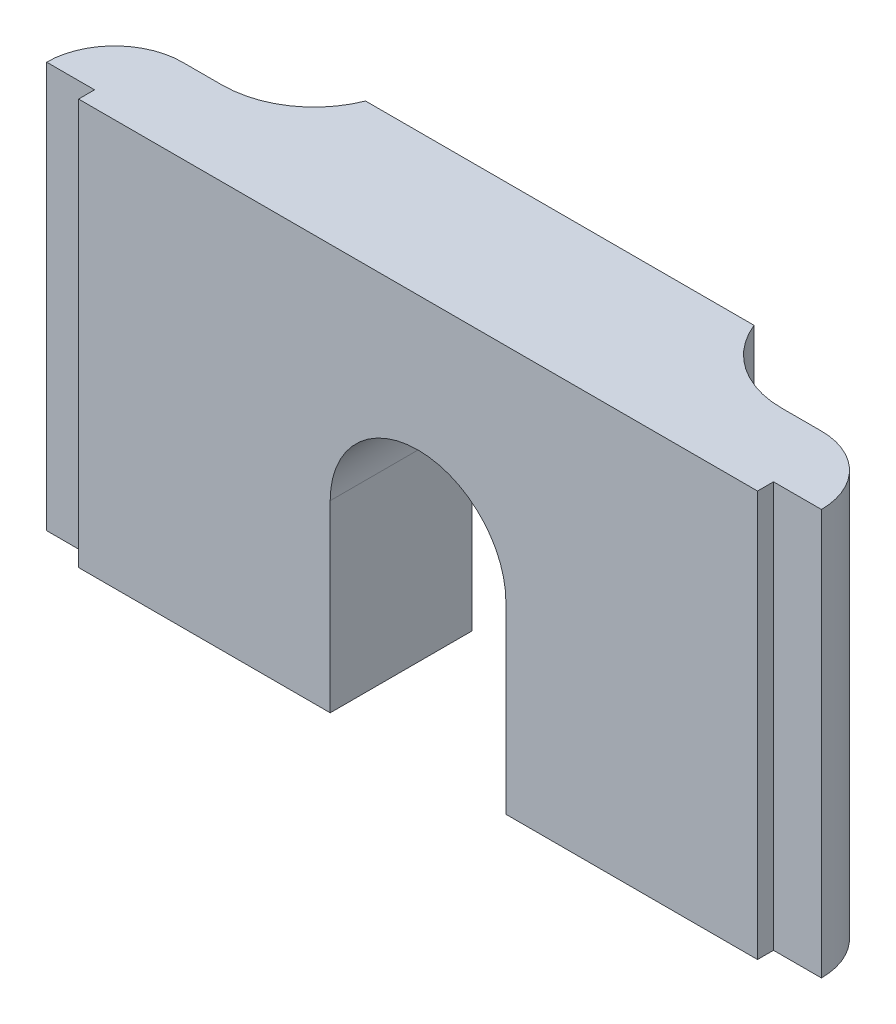
SolidWorks part; units mm, degrees
ref_plane "Front Plane" through (0, 0, 0) normal (0, 0, 1) x (1, 0, 0)
ref_plane "Top Plane" through (0, 0, 0) normal (0, 1, 0) x (1, 0, 0)
ref_plane "Right Plane" through (0, 0, 0) normal (1, 0, 0) x (0, 0, -1)
sketch "Sketch1" plane through (0, 0, 0) normal (0, 1, 0) x (1, 0, 0)
  line L0 (-24.3193, 0) -> (24.3193, 0)
  line L1 (35.0051, -7.25) -> (40, -7.25)
  line L2 (48.5, -15.75) -> (42.5, -15.75)
  line L3 (42.5, -15.75) -> (42.5, -17.75)
  line L4 (42.5, -17.75) -> (-42.5, -17.75)
  line L5 (0, 16.8687) -> (0, -34.2856) construction
  line L6 (-42.5, -15.75) -> (-42.5, -17.75)
  line L7 (-48.5, -15.75) -> (-42.5, -15.75)
  line L8 (-35.0051, -7.25) -> (-40, -7.25)
  arc A0 (24.3193, 0) -> (35.0051, -7.25) centre (35.0051, 4.25) ccw
  arc A1 (48.5, -15.75) -> (40, -7.25) centre (40, -15.75) ccw
  arc A2 (-48.5, -15.75) -> (-40, -7.25) centre (-40, -15.75) cw
  arc A3 (-24.3193, 0) -> (-35.0051, -7.25) centre (-35.0051, 4.25) cw
  point P20 (0, -17.75)
  point P21 (0, 0)
extrude "Boss-Extrude1" add sketch "Sketch1" along normal blind 50.8
sketch "Sketch3" plane through (0, 0, 17.75) normal (0, 0, 1) x (1, 0, 0)
  line L0 (0, 0) -> (0, 57.7368) construction
  line L1 (-11, 23) -> (-11, 0)
  line L2 (-42.5, 0) -> (42.5, 0) construction
  line L3 (-11, 0) -> (11, 0)
  line L4 (11, 0) -> (11, 23)
  arc A0 (11, 23) -> (-11, 23) centre (0, 23) ccw
extrude "Cut-Extrude1" cut sketch "Sketch3" against normal through all
